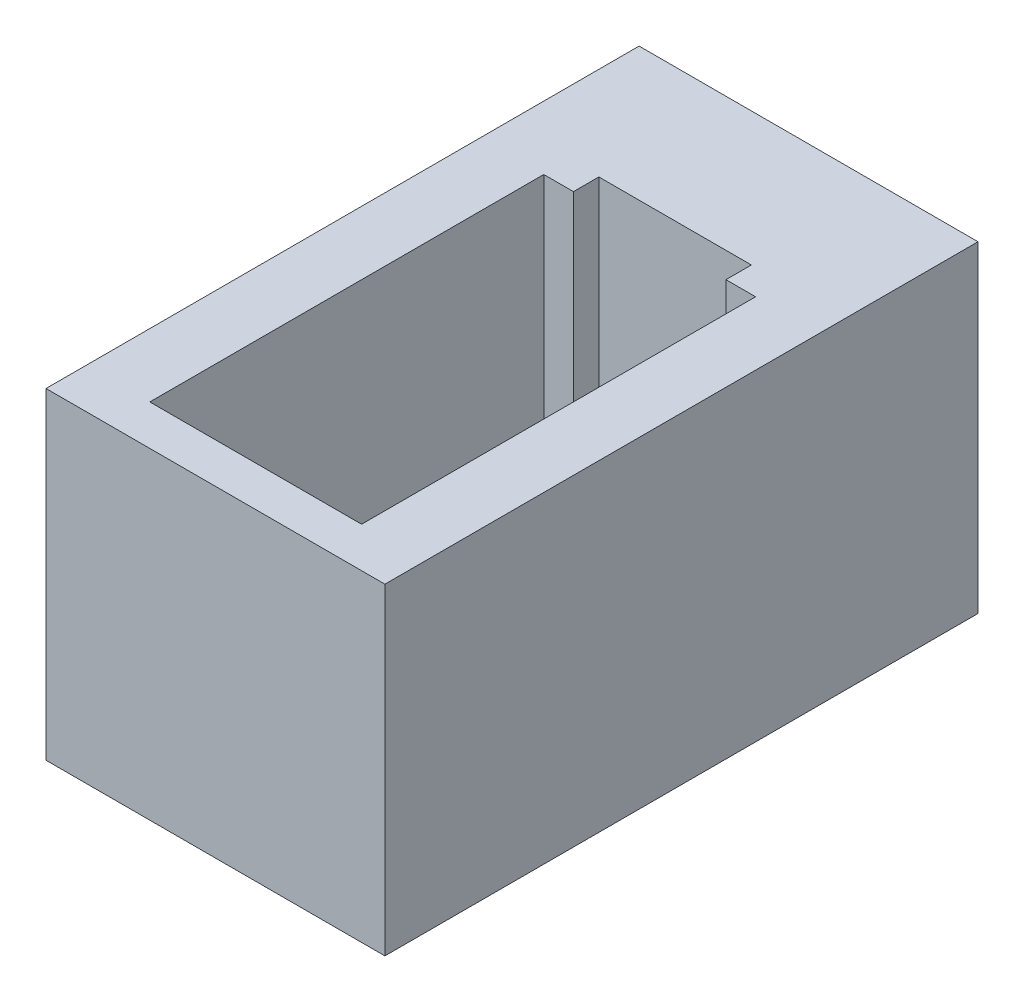
SolidWorks part; units mm, degrees
ref_plane "Front Plane" through (0, 0, 0) normal (0, 0, 1) x (1, 0, 0)
ref_plane "Top Plane" through (0, 0, 0) normal (0, 1, 0) x (1, 0, 0)
ref_plane "Right Plane" through (0, 0, 0) normal (1, 0, 0) x (0, 0, -1)
sketch "Sketch2" plane through (0, 0, 0) normal (0, 1, 0) x (1, 0, 0)
  line L1 (-10, 14) -> (10, 14)
  line L2 (-10, 14) -> (-10, -14)
  line L3 (-10, -14) -> (10, -14)
  line L4 (10, 14) -> (10, -14)
  line L5 (-10, 14) -> (10, -14) construction
  line L6 (-10, -14) -> (10, 14) construction
  point P0 (0, 0)
  dimension "D1" = 28
  dimension "D2" = 20
extrude "Boss-Extrude1" add sketch "Sketch2" along normal blind 19
sketch "Sketch3" plane through (0, 19, 0) normal (0, 1, 0) x (1, 0, 0)
  line L1 (-6.25, 11.625) -> (6.25, 11.625)
  line L2 (-6.25, 11.625) -> (-6.25, -11.625)
  line L3 (-6.25, -11.625) -> (6.25, -11.625)
  line L4 (6.25, 11.625) -> (6.25, -11.625)
  line L5 (-6.25, 11.625) -> (6.25, -11.625) construction
  line L6 (-6.25, -11.625) -> (6.25, 11.625) construction
  point P0 (0, 0)
  dimension "D1" = 12.5
  dimension "D2" = 23.25
extrude "Cut-Extrude1" cut sketch "Sketch3" against normal blind 16
sketch "Sketch4" plane through (0, 0, -14) normal (0, 0, -1) x (-1, 0, 0)
  line L1 (-10, 19) -> (10, 19)
  line L2 (-10, 19) -> (-10, 0)
  line L3 (-10, 0) -> (10, 0)
  line L4 (10, 19) -> (10, 0)
extrude "Boss-Extrude3" add sketch "Sketch4" along normal blind 7
sketch "Sketch5" plane through (0, 0, 0) normal (0, -1, 0) x (1, 0, 0)
  line L0 (0, -13.125) -> (0, -21) construction
  line L1 (4.5, -13.125) -> (-4.5, -13.125)
  line L2 (4.5, -13.125) -> (4.5, -8.125)
  line L3 (4.5, -8.125) -> (-4.5, -8.125)
  line L4 (-4.5, -13.125) -> (-4.5, -8.125)
  line L5 (10, -21) -> (-10, -21) construction
  line L6 (6.25, -11.625) -> (-6.25, -11.625) construction
  dimension "D1" = 9
  dimension "D2" = 5
  dimension "D3" = 1.5
extrude "Cut-Extrude2" cut sketch "Sketch5" against normal through all
